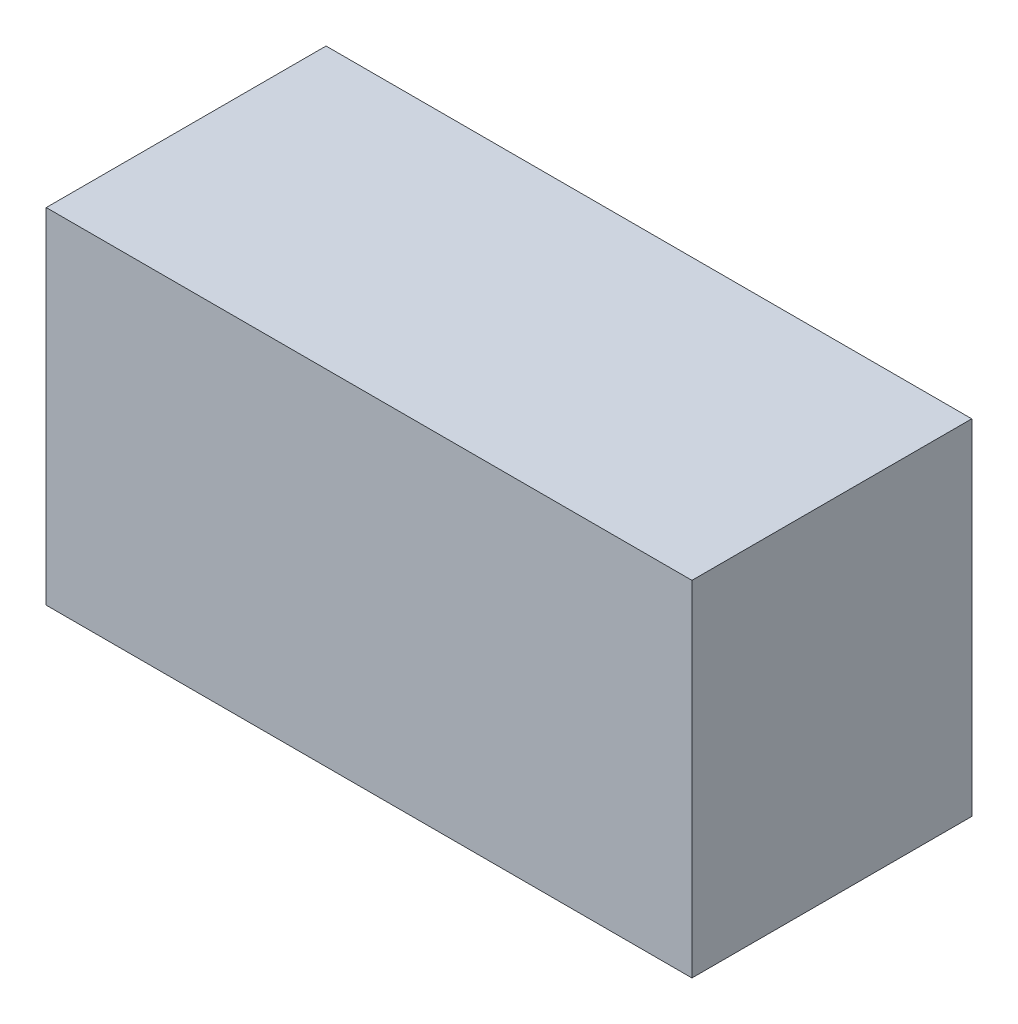
SolidWorks part; units mm, degrees
ref_plane "前视基准面" through (0, 0, 0) normal (0, 0, 1) x (1, 0, 0)
ref_plane "上视基准面" through (0, 0, 0) normal (0, 1, 0) x (1, 0, 0)
ref_plane "右视基准面" through (0, 0, 0) normal (1, 0, 0) x (0, 0, -1)
other "Configuration Table"
sketch "草图1" plane through (0, 0, 0) normal (0, 0, 1) x (1, 0, 0)
  line L1 (-30, -16) -> (30, -16)
  line L2 (-30, -16) -> (-30, 16)
  line L3 (-30, 16) -> (30, 16)
  line L4 (30, -16) -> (30, 16)
  line L5 (-30, -16) -> (30, 16) construction
  line L6 (-30, 16) -> (30, -16) construction
  point P0 (0, 0)
extrude "凸台-拉伸1" add sketch "草图1" along normal blind 26
